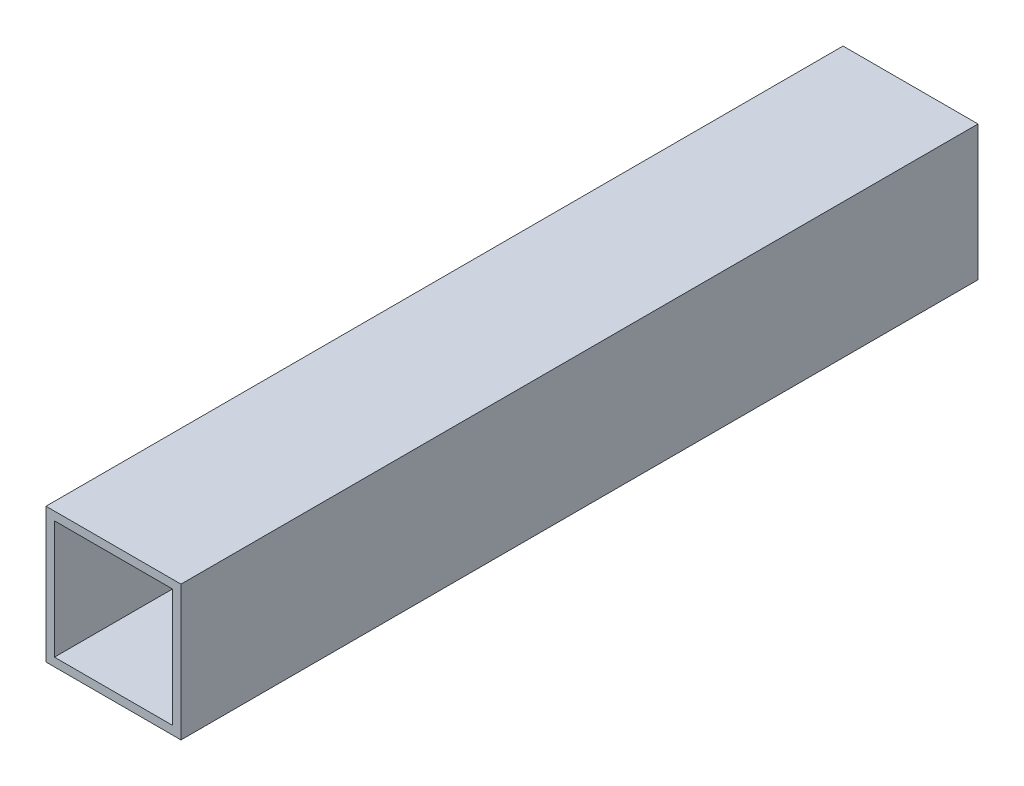
SolidWorks part; units mm, degrees
material "6061-T6 (SS)"
ref_plane "Front Plane" through (0, 0, 0) normal (0, 0, 1) x (1, 0, 0)
ref_plane "Top Plane" through (0, 0, 0) normal (0, 1, 0) x (1, 0, 0)
ref_plane "Right Plane" through (0, 0, 0) normal (1, 0, 0) x (0, 0, -1)
sketch "Sketch1" plane through (0, 0, 0) normal (0, 0, 1) x (1, 0, 0)
  line L1 (12.7, -12.7) -> (-12.7, -12.7)
  line L2 (12.7, -12.7) -> (12.7, 12.7)
  line L3 (12.7, 12.7) -> (-12.7, 12.7)
  line L4 (-12.7, -12.7) -> (-12.7, 12.7)
  line L5 (12.7, -12.7) -> (-12.7, 12.7) construction
  line L6 (12.7, 12.7) -> (-12.7, -12.7) construction
  line L7 (11.1125, -11.1125) -> (-11.1125, -11.1125)
  line L8 (11.1125, -11.1125) -> (11.1125, 11.1125)
  line L9 (11.1125, 11.1125) -> (-11.1125, 11.1125)
  line L10 (-11.1125, -11.1125) -> (-11.1125, 11.1125)
  line L11 (11.1125, -11.1125) -> (-11.1125, 11.1125) construction
  line L12 (11.1125, 11.1125) -> (-11.1125, -11.1125) construction
  point P0 (0, 0)
  point P6 (0, 0)
  point P11 (-12.7, 0)
  dimension "D1" = 25.4
  dimension "D2" = 25.4
  dimension "D3" = 1.5875
  dimension "D4" = 1.5875
extrude "Boss-Extrude1" add sketch "Sketch1" along normal mid plane 150
